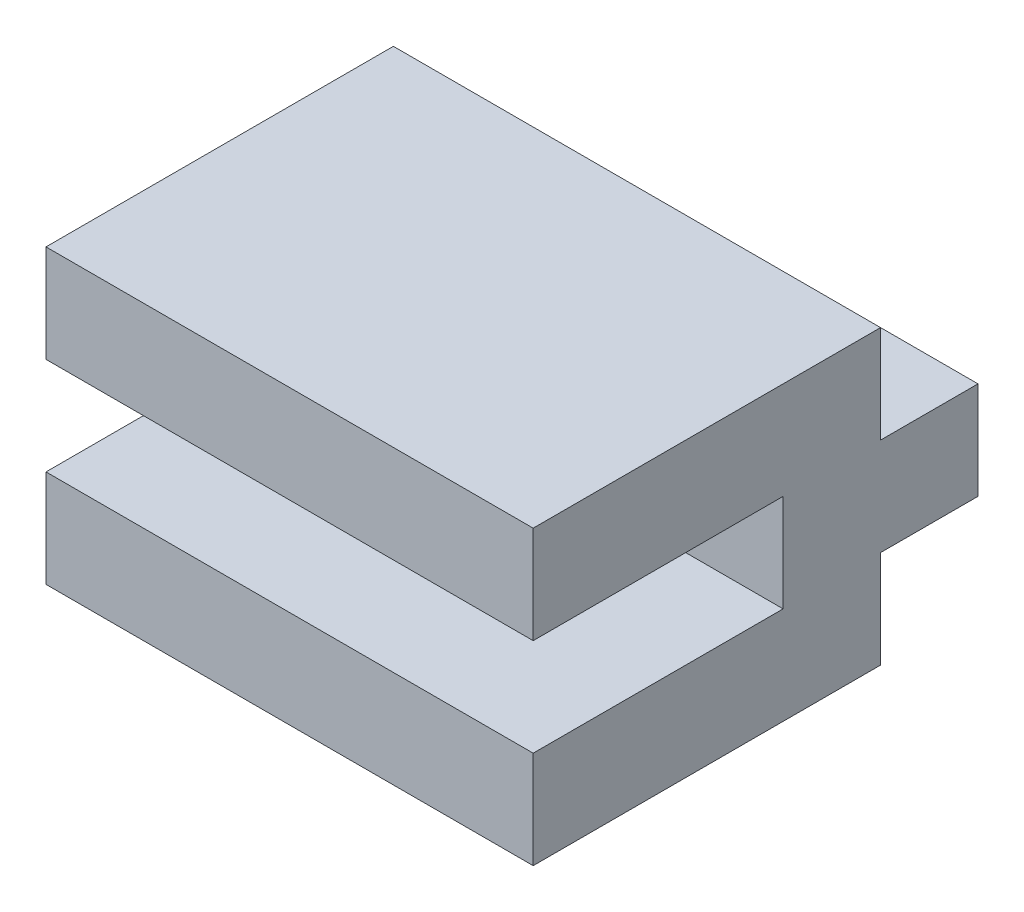
SolidWorks part; units mm, degrees
ref_plane "前视基准面" through (0, 0, 0) normal (0, 0, 1) x (1, 0, 0)
ref_plane "上视基准面" through (0, 0, 0) normal (0, 1, 0) x (1, 0, 0)
ref_plane "右视基准面" through (0, 0, 0) normal (1, 0, 0) x (0, 0, -1)
sketch "Sketch1" plane through (0, 0, 0) normal (1, 0, 0) x (0, 0, -1)
  line L0 (0, 0) -> (-3.5653, 0) construction
  line L1 (3.5653, -3) -> (-3.5653, -3)
  line L2 (3.5653, -3) -> (3.5653, -1)
  line L3 (3.5653, 3) -> (-3.5653, 3)
  line L4 (-3.5653, -3) -> (-3.5653, -1)
  line L5 (3.5653, -3) -> (-3.5653, 3) construction
  line L6 (3.5653, 3) -> (-3.5653, -3) construction
  line L7 (0, 0) -> (10.0087, 0) construction
  line L8 (1.5653, -1) -> (-3.5653, -1)
  line L9 (1.5653, -1) -> (1.5653, 1)
  line L10 (1.5653, 1) -> (-3.5653, 1)
  line L12 (1.5653, -1) -> (-3.5653, 1) construction
  line L13 (1.5653, 1) -> (-3.5653, -1) construction
  line L14 (-3.5653, 1) -> (-3.5653, 3)
  line L15 (5.5653, -1) -> (3.5653, -1)
  line L16 (5.5653, -1) -> (5.5653, 1)
  line L17 (5.5653, 1) -> (3.5653, 1)
  line L19 (5.5653, -1) -> (3.5653, 1) construction
  line L20 (5.5653, 1) -> (3.5653, -1) construction
  line L21 (3.5653, 1) -> (3.5653, 3)
  point P0 (0, 0)
  point P8 (-1, 0)
  point P13 (4.5653, 0)
  dimension "D1" = 2
  dimension "D2" = 2
  dimension "D3" = 2
  dimension "D4" = 2
  dimension "D5" = 2
extrude "Boss-Extrude1" add sketch "Sketch1" along normal blind 10
